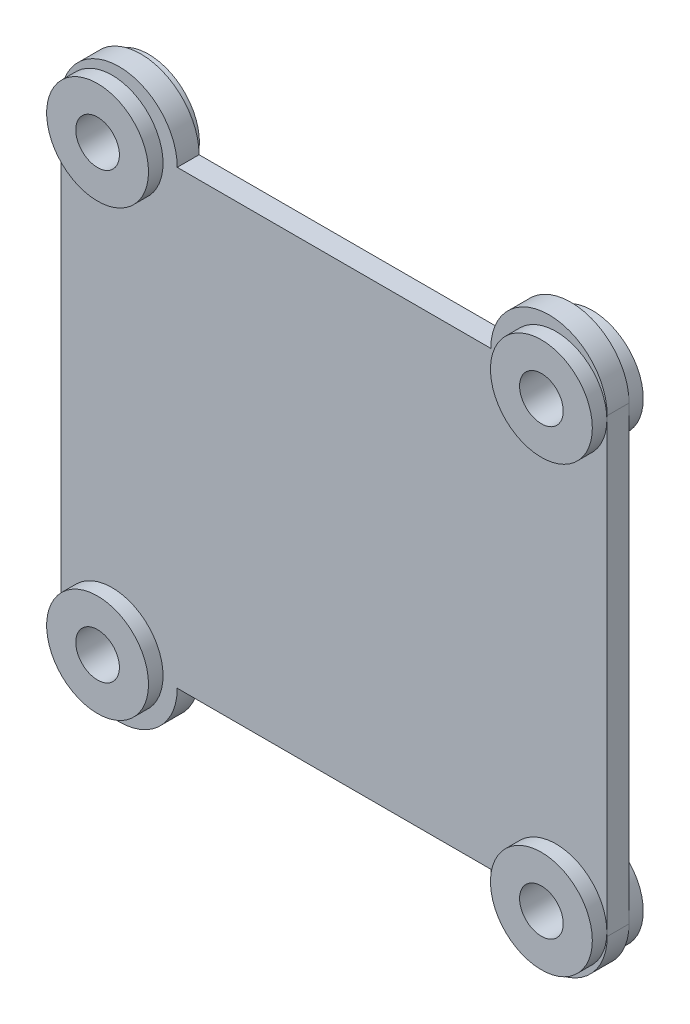
SolidWorks part; units mm, degrees
ref_plane "Alzado" through (0, 0, 0) normal (0, 0, 1) x (1, 0, 0)
ref_plane "Planta" through (0, 0, 0) normal (0, 1, 0) x (1, 0, 0)
ref_plane "Vista lateral" through (0, 0, 0) normal (1, 0, 0) x (0, 0, -1)
sketch "Croquis1" plane through (0, 0, 0) normal (0, 0, 1) x (1, 0, 0)
  line L20 (17.8832, 13.696) -> (17.8832, -17.304)
  line L35 (-19.6668, 13.696) -> (-19.6668, -17.304)
  line L36 (-11.6668, 13.696) -> (9.8832, 13.696)
  line L37 (-19.6668, -1.804) -> (17.8832, -1.804) construction
  line L38 (-11.6668, -17.304) -> (9.8832, -17.304)
  circle A0 centre (-16.1418, 13.446) radius 2.5
  circle A1 centre (14.3582, 13.446) radius 2.5
  circle A2 centre (14.3582, -17.054) radius 2.5
  circle A3 centre (-16.1418, -17.054) radius 2.5
  arc A12 (-11.6668, 13.696) -> (-19.6668, 13.696) centre (-15.6668, 13.696) ccw
  arc A13 (17.8832, 13.696) -> (9.8832, 13.696) centre (13.8832, 13.696) ccw
  arc A14 (17.8832, -17.304) -> (9.8832, -17.304) centre (13.8832, -17.304) cw
  arc A15 (-11.6668, -17.304) -> (-19.6668, -17.304) centre (-15.6668, -17.304) cw
  point P54 (17.8832, 17.696)
  point P57 (-19.6668, 17.696)
  dimension "D3" = 2
  dimension "D1" = 37.55
  dimension "D4" = 2
extrude "Saliente-Extruir1" add sketch "Croquis1" along normal blind 1.5
sketch "Croquis2" plane through (0, 0, 1.5) normal (0, 0, 1) x (1, 0, 0)
  line L1 (-18.6418, -17.054) -> (-13.6418, -17.054)
  circle A1 centre (-16.1418, -17.054) radius 2.5 construction
ref_plane "Plano1" through (0, -17.054, 0) normal (0, -1, 0) x (-1, 0, 0)
sketch "Croquis3" plane through (0, -17.054, 0) normal (0, -1, 0) x (-1, 0, 0)
  line L0 (18.6418, -1.5) -> (19.6418, -1.5)
  line L1 (19.6418, -1.5) -> (19.6418, -2.5)
  line L2 (18.6418, -1.5) -> (13.6418, -1.5) construction
  line L3 (16.1418, -1.5) -> (16.1418, -2.5) construction
  line L5 (16.1418, -2.5) -> (16.1418, 1) construction
  line L7 (19.6418, 1) -> (19.6418, 0)
  line L8 (19.6418, 0) -> (18.6418, 0)
  line L9 (18.6418, 0) -> (18.6418, -1.5)
  line L10 (19.6418, -2.5) -> (17.6418, -2.5)
  line L11 (17.6418, -2.5) -> (17.6418, 1)
  line L12 (17.6418, 1) -> (19.6418, 1)
  dimension "D1" = 1
  dimension "D2" = 1
  dimension "D3" = 1
  dimension "D4" = 1
  dimension "D5" = 3.5
  dimension "D6" = 2
revolve "Revolución1" add sketch "Croquis3" angle 360 about L5
pattern_linear "MatrizL1" count 2 spacing 30.5 along (1, 0, 0) count 2 spacing 30.5 along (0, 1, 0) of "Revolución1"
